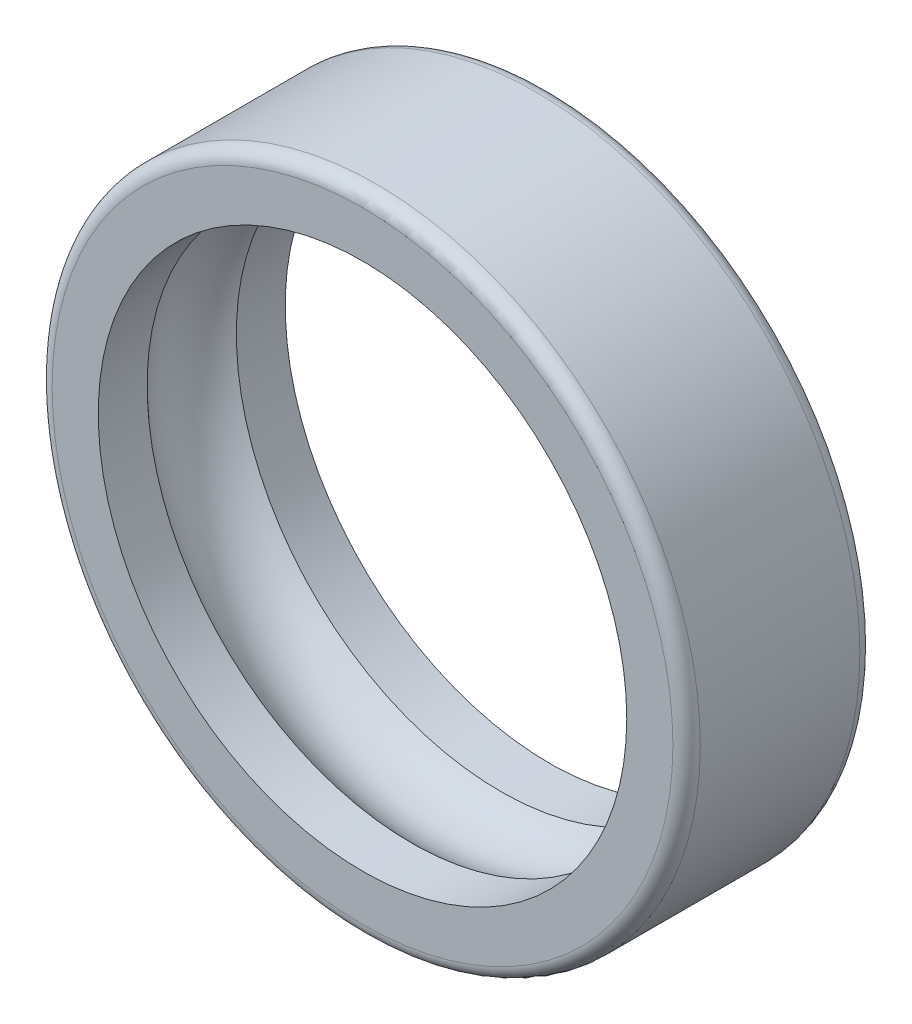
SolidWorks part; units mm, degrees
ref_plane "Plan de face" through (0, 0, 0) normal (0, 0, 1) x (1, 0, 0)
ref_plane "Plan de dessus" through (0, 0, 0) normal (0, 1, 0) x (1, 0, 0)
ref_plane "Plan de droite" through (0, 0, 0) normal (1, 0, 0) x (0, 0, -1)
sketch "Esquisse1" plane through (0, 0, 0) normal (1, 0, 0) x (0, 0, -1)
  line L0 (0, 0) -> (0, 21.2) construction
  line L1 (0, 18) -> (-8.189, 18) construction
  line L2 (-7.5, 21.2) -> (7.5, 21.2)
  line L3 (-7.5, 21.2) -> (-7.5, 26)
  line L4 (-7.5, 26) -> (7.5, 26)
  line L5 (7.5, 21.2) -> (7.5, 26)
  line L6 (0, 0) -> (6.1355, 0) construction
  circle A0 centre (0, 18) radius 4.8
  dimension "D1" = 9.6
  dimension "D2" = 26
  dimension "D3" = 21.2
  dimension "D4" = 18
  dimension "D5" = 15
revolve "Révolution1" add sketch "Esquisse1" angle 360 about L6
fillet "Congé1" radius 1.1 2 edges at (26, 0, 7.5) (26, 0, -7.5)
scale "Echelle1" scale about centroid uniform scaling yes scale factor 0.69
